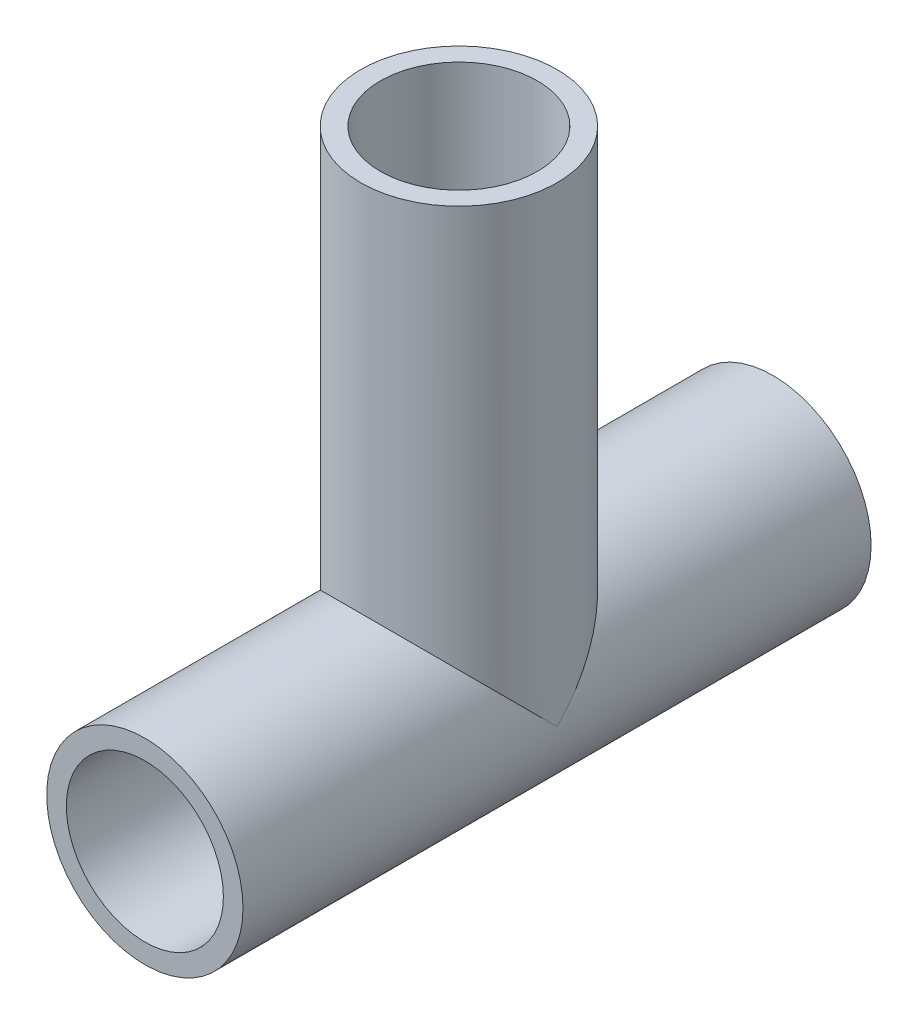
SolidWorks part; units mm, degrees
ref_plane "前视基准面" through (0, 0, 0) normal (0, 0, 1) x (1, 0, 0)
ref_plane "上视基准面" through (0, 0, 0) normal (0, 1, 0) x (1, 0, 0)
ref_plane "右视基准面" through (0, 0, 0) normal (1, 0, 0) x (0, 0, -1)
sketch "草图1" plane through (0, 0, 0) normal (0, 0, 1) x (1, 0, 0)
  circle A0 centre (0, 0) radius 12.5
  circle A1 centre (0, 0) radius 10
  dimension "D1" = 25
  dimension "D2" = 20
extrude "凸台-拉伸1" add sketch "草图1" along normal mid plane 80
ref_plane "基准面1" through (0, 60, 0) normal (0, 1, 0) x (1, 0, 0)
sketch "草图2" plane through (0, 60, 0) normal (0, 1, 0) x (1, 0, 0)
  circle A0 centre (0, 0) radius 12.5
  circle A1 centre (0, 0) radius 10
  dimension "D1" = 25
  dimension "D2" = 20
extrude "凸台-拉伸2" add sketch "草图2" against normal up to surface (47.5 mm away)
sketch "草图3" plane through (0, 60, 0) normal (0, 1, 0) x (1, 0, 0)
  circle A0 centre (0, 0) radius 10
  dimension "D1" = 20
extrude "切除-拉伸1" cut sketch "草图3" against normal blind 60
